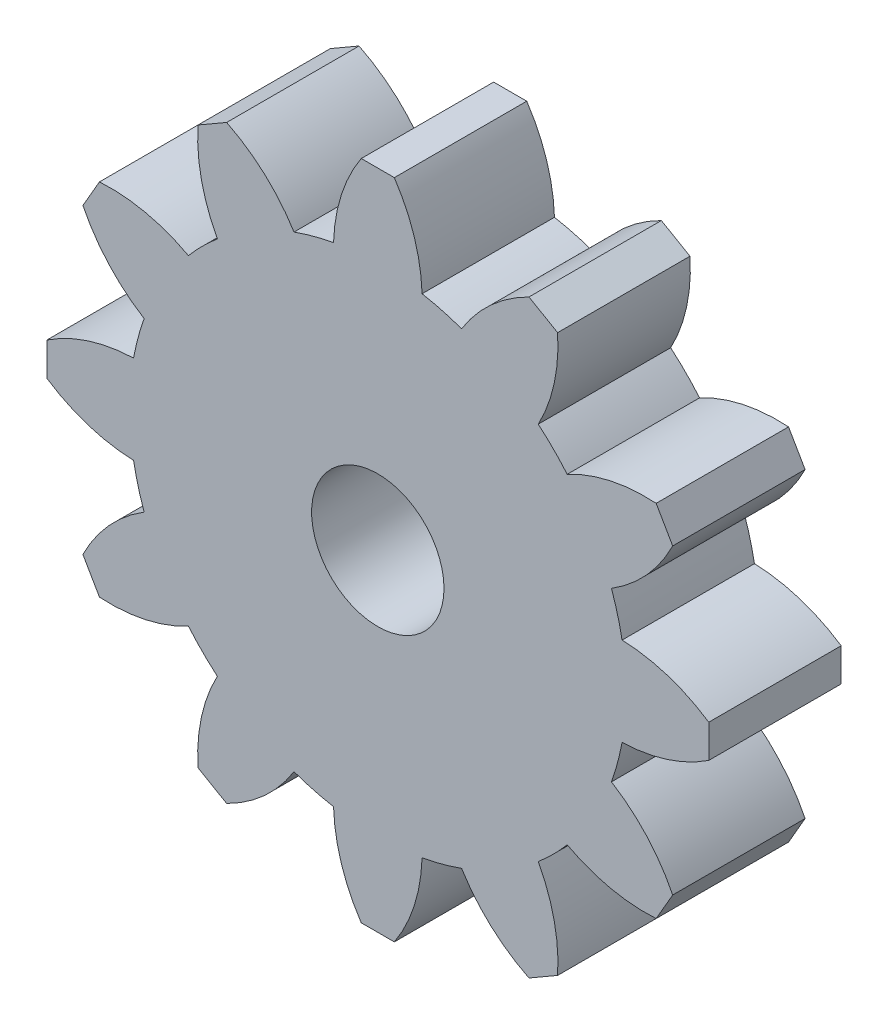
SolidWorks part; units mm, degrees
material "Brass"
ref_plane "Front Plane" through (0, 0, 0) normal (0, 0, 1) x (1, 0, 0)
ref_plane "Top Plane" through (0, 0, 0) normal (0, 1, 0) x (1, 0, 0)
ref_plane "Right Plane" through (0, 0, 0) normal (1, 0, 0) x (0, 0, -1)
sketch "Sketch1" plane through (0, 0, 0) normal (0, 0, 1) x (1, 0, 0)
  line L0 (-1, 20) -> (1, 20)
  line L1 (-2.675, 14.7596) -> (2.675, 14.7596) construction
  line L2 (9.134, 17.8205) -> (10.866, 16.8205)
  line L3 (16.8205, 10.866) -> (17.8205, 9.134)
  line L4 (20, 1) -> (20, -1)
  line L5 (17.8205, -9.134) -> (16.8205, -10.866)
  line L6 (10.866, -16.8205) -> (9.134, -17.8205)
  line L7 (1, -20) -> (-1, -20)
  line L8 (-9.134, -17.8205) -> (-10.866, -16.8205)
  line L9 (-16.8205, -10.866) -> (-17.8205, -9.134)
  line L10 (-20, -1) -> (-20, 1)
  line L11 (-17.8205, 9.134) -> (-16.8205, 10.866)
  line L12 (-10.866, 16.8205) -> (-9.134, 17.8205)
  circle A0 centre (0, 0) radius 4
  arc A1 (-9.6964, 11.4446) -> (-11.4446, 9.6964) centre (0, 0) ccw
  arc A2 (-1, 20) -> (-2.675, 14.7596) centre (7.3203, 14.4527) ccw
  arc A3 (1, 20) -> (2.675, 14.7596) centre (-7.3203, 14.4527) cw
  arc A4 (9.134, 17.8205) -> (5.0632, 14.1196) centre (13.5659, 8.8562) ccw
  arc A5 (10.866, 16.8205) -> (9.6964, 11.4446) centre (0.8868, 16.1765) cw
  arc A6 (16.8205, 10.866) -> (11.4446, 9.6964) centre (16.1765, 0.8868) ccw
  arc A7 (17.8205, 9.134) -> (14.1196, 5.0632) centre (8.8562, 13.5659) cw
  arc A8 (20, 1) -> (14.7596, 2.675) centre (14.4527, -7.3203) ccw
  arc A9 (20, -1) -> (14.7596, -2.675) centre (14.4527, 7.3203) cw
  arc A10 (17.8205, -9.134) -> (14.1196, -5.0632) centre (8.8562, -13.5659) ccw
  arc A11 (16.8205, -10.866) -> (11.4446, -9.6964) centre (16.1765, -0.8868) cw
  arc A12 (10.866, -16.8205) -> (9.6964, -11.4446) centre (0.8868, -16.1765) ccw
  arc A13 (9.134, -17.8205) -> (5.0632, -14.1196) centre (13.5659, -8.8562) cw
  arc A14 (1, -20) -> (2.675, -14.7596) centre (-7.3203, -14.4527) ccw
  arc A15 (-1, -20) -> (-2.675, -14.7596) centre (7.3203, -14.4527) cw
  arc A16 (-9.134, -17.8205) -> (-5.0632, -14.1196) centre (-13.5659, -8.8562) ccw
  arc A17 (-10.866, -16.8205) -> (-9.6964, -11.4446) centre (-0.8868, -16.1765) cw
  arc A18 (-16.8205, -10.866) -> (-11.4446, -9.6964) centre (-16.1765, -0.8868) ccw
  arc A19 (-17.8205, -9.134) -> (-14.1196, -5.0632) centre (-8.8562, -13.5659) cw
  arc A20 (-20, -1) -> (-14.7596, -2.675) centre (-14.4527, 7.3203) ccw
  arc A21 (-20, 1) -> (-14.7596, 2.675) centre (-14.4527, -7.3203) cw
  arc A22 (-17.8205, 9.134) -> (-14.1196, 5.0632) centre (-8.8562, 13.5659) ccw
  arc A23 (-16.8205, 10.866) -> (-11.4446, 9.6964) centre (-16.1765, 0.8868) cw
  arc A24 (-10.866, 16.8205) -> (-9.6964, 11.4446) centre (-0.8868, 16.1765) ccw
  arc A25 (-9.134, 17.8205) -> (-5.0632, 14.1196) centre (-13.5659, 8.8562) cw
  arc A26 (-14.1196, 5.0632) -> (-14.7596, 2.675) centre (0, 0) ccw
  arc A27 (-14.7596, -2.675) -> (-14.1196, -5.0632) centre (0, 0) ccw
  arc A28 (-11.4446, -9.6964) -> (-9.6964, -11.4446) centre (0, 0) ccw
  arc A29 (-5.0632, -14.1196) -> (-2.675, -14.7596) centre (0, 0) ccw
  arc A30 (2.675, -14.7596) -> (5.0632, -14.1196) centre (0, 0) ccw
  arc A31 (9.6964, -11.4446) -> (11.4446, -9.6964) centre (0, 0) ccw
  arc A32 (14.1196, -5.0632) -> (14.7596, -2.675) centre (0, 0) ccw
  arc A33 (14.7596, 2.675) -> (14.1196, 5.0632) centre (0, 0) ccw
  arc A34 (11.4446, 9.6964) -> (9.6964, 11.4446) centre (0, 0) ccw
  arc A35 (5.0632, 14.1196) -> (2.675, 14.7596) centre (0, 0) ccw
  arc A36 (-2.675, 14.7596) -> (-5.0632, 14.1196) centre (0, 0) ccw
  point P6 (0, 20)
  point P11 (0, 14.7596)
  point P80 (0, 0)
  dimension "D1" = 8
  dimension "D2" = 30
  dimension "D5" = 10
  dimension "D3" = 20
  dimension "D4" = 2
  dimension "D6" = 5.35
  dimension "D7" = 12
extrude "Boss-Extrude1" add sketch "Sketch1" along normal blind 8
